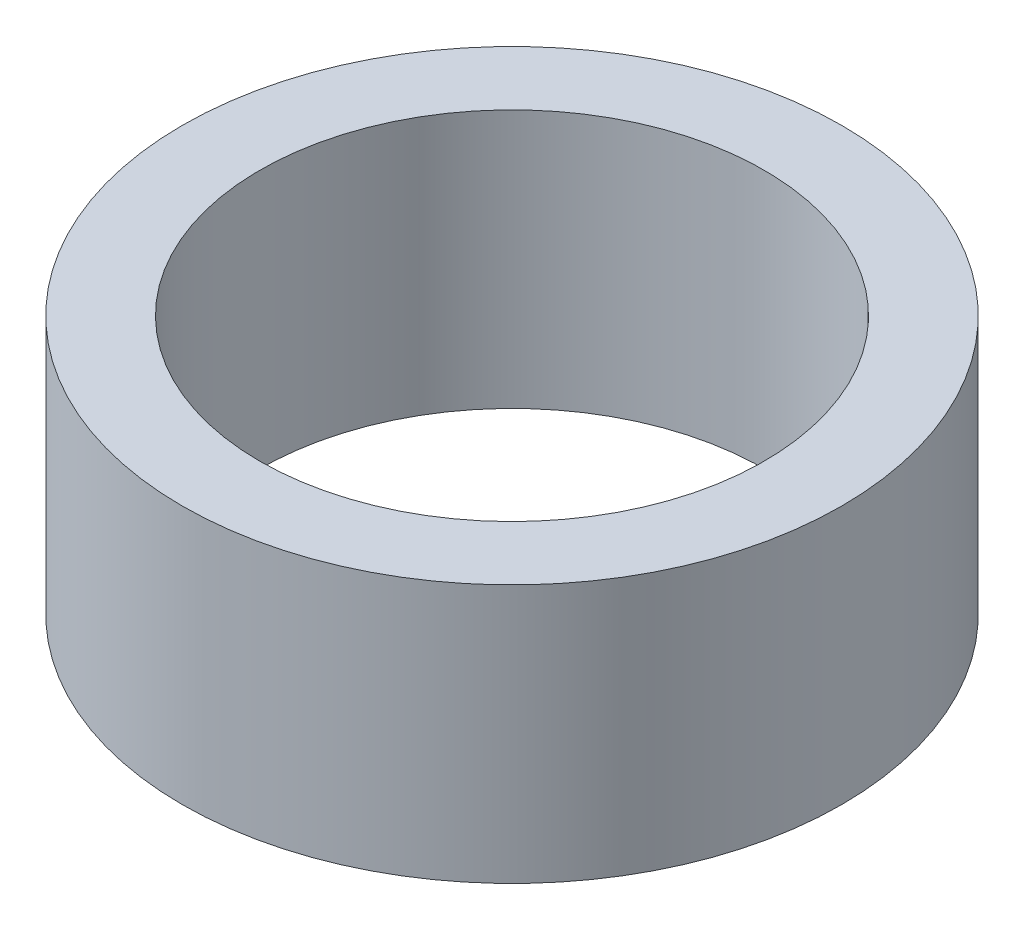
SolidWorks part; units mm, degrees
ref_plane "Front Plane" through (0, 0, 0) normal (0, 0, 1) x (1, 0, 0)
ref_plane "Top Plane" through (0, 0, 0) normal (0, 1, 0) x (1, 0, 0)
ref_plane "Right Plane" through (0, 0, 0) normal (1, 0, 0) x (0, 0, -1)
sketch "Sketch1" plane through (0, 0, 0) normal (0, 1, 0) x (1, 0, 0)
  circle A0 centre (0, 0) radius 9.75
  circle A1 centre (0, 0) radius 12.75
  dimension "D1" = 19.5
  dimension "D2" = 3
extrude "Boss-Extrude1" add sketch "Sketch1" along normal blind 10
